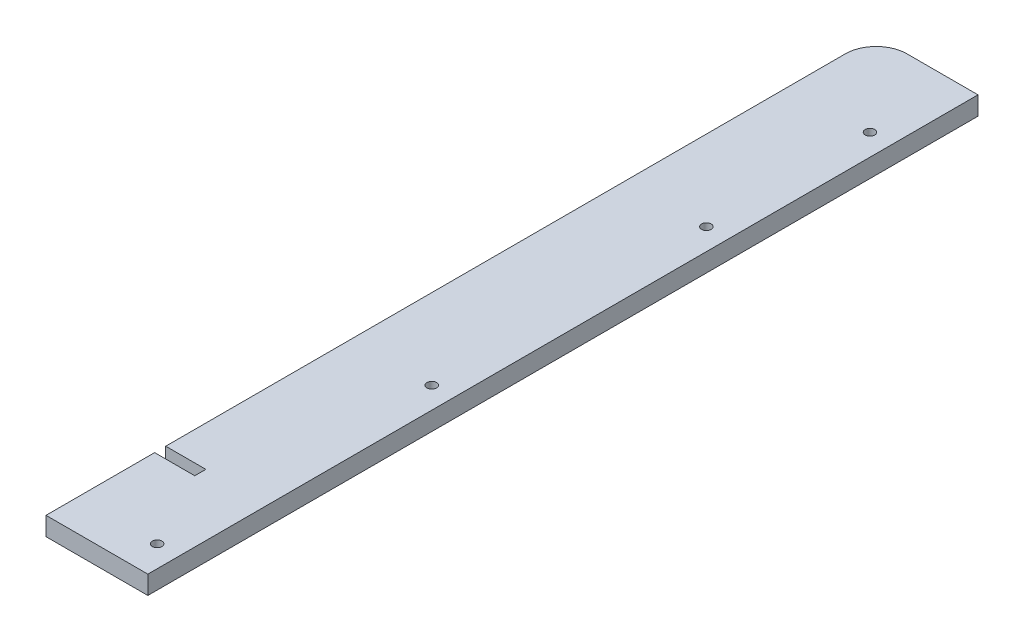
SolidWorks part; units mm, degrees
ref_plane "Płaszczyzna przednia" through (0, 0, 0) normal (0, 0, 1) x (1, 0, 0)
ref_plane "Płaszczyzna górna" through (0, 0, 0) normal (0, 1, 0) x (1, 0, 0)
ref_plane "Płaszczyzna prawa" through (0, 0, 0) normal (1, 0, 0) x (0, 0, -1)
sketch "Szkic2" plane through (0, 1505.9474, 0) normal (0, 1, 0) x (0, 0, 1)
  line L0 (-183.9552, 693.685) -> (-183.9552, -158.315)
  line L1 (-183.9552, 693.685) -> (103.0448, 693.685)
  line L2 (-183.9552, -158.315) -> (103.0448, -158.315)
  line L3 (103.0448, 693.685) -> (103.0448, -158.315)
  dimension "D1" = 852
  dimension "D2" = 287
extrude "Dodanie-wyciągnięcie1" add sketch "Szkic2" along normal blind 6
sketch "Szkic3" plane through (0, 1511.9474, 0) normal (0, 1, 0) x (1, 0, 0)
  line L14 (673.685, -83.0448) -> (673.685, 163.9552)
  line L15 (-138.315, -83.0448) -> (673.685, -83.0448)
  line L16 (673.685, 163.9552) -> (-138.315, 163.9552)
  line L17 (-138.315, 163.9552) -> (-138.315, -83.0448)
  line L18 (673.685, -73.0448) -> (673.685, 153.9552)
  line L19 (-128.315, -83.0448) -> (663.685, -83.0448)
  line L20 (663.685, 163.9552) -> (-128.315, 163.9552)
  line L21 (-138.315, 153.9552) -> (-138.315, -73.0448)
  arc A0 (673.685, 153.9552) -> (663.685, 163.9552) centre (663.685, 153.9552) ccw
  arc A1 (673.685, -73.0448) -> (663.685, -83.0448) centre (663.685, -73.0448) cw
  arc A2 (-128.315, -83.0448) -> (-138.315, -73.0448) centre (-128.315, -73.0448) cw
  arc A3 (-128.315, 163.9552) -> (-138.315, 153.9552) centre (-128.315, 153.9552) ccw
  dimension "D2" = 10
  dimension "D1" = 20
extrude "Wytnij-wyciągnięcie1" cut sketch "Szkic3" against normal blind 10
sketch "Szkic5" plane through (0, 1511.9474, 0) normal (0, 1, 0) x (1, 0, 0)
  line L0 (-158.315, -103.0448) -> (693.685, -103.0448) construction
  line L1 (-158.315, 183.9552) -> (-138.315, 183.9552)
  line L2 (-158.315, 183.9552) -> (-158.315, -103.0448)
  line L3 (-158.315, -103.0448) -> (-138.315, -103.0448)
  line L4 (-138.315, 183.9552) -> (-138.315, -103.0448)
  line L5 (-138.315, 153.9552) -> (-138.315, -73.0448) construction
  line L6 (693.685, 183.9552) -> (-158.315, 183.9552) construction
  dimension "D1" = 0
extrude "Wytnij-wyciągnięcie3" cut sketch "Szkic5" against normal through all flip side to cut
other "Przenieś ścianę1" face at (-158.315, 1508.9474, -40.4552) parameters "D1"=13
sketch "Szkic6" plane through (0, 1511.9474, 0) normal (0, 1, 0) x (1, 0, 0)
  line L0 (-138.315, 183.9552) -> (-138.315, -103.0448) construction
  line L1 (-171.315, 183.9552) -> (-138.315, 183.9552)
  line L2 (-171.315, 183.9552) -> (-171.315, 165.9552)
  line L3 (-171.315, 165.9552) -> (-138.315, 165.9552)
  line L4 (-138.315, 183.9552) -> (-138.315, 165.9552)
  dimension "D1" = 18
extrude "Wytnij-wyciągnięcie4" cut sketch "Szkic6" against normal blind 10
sketch "Szkic8" plane through (0, 1505.9474, 0) normal (0, -1, 0) x (1, 0, 0)
  line L0 (-161.315, -165.9552) -> (-171.315, -165.9552)
  line L2 (-171.315, -165.9552) -> (-171.315, -155.9552)
  arc A0 (-161.315, -165.9552) -> (-171.315, -155.9552) centre (-161.315, -155.9552) cw
  point P10 (-171.315, -165.9552)
  dimension "D1" = 10
extrude "Wytnij-wyciągnięcie6" cut sketch "Szkic8" against normal through all
sketch "Szkic9" plane through (0, 1511.9474, 0) normal (0, 1, 0) x (1, 0, 0)
  circle A0 centre (-145.315, -93.0448) radius 1.55 construction
  circle A1 centre (-145.315, -4.0448) radius 1.55 construction
  circle A2 centre (-145.315, 84.9552) radius 1.55 construction
  circle A3 centre (-145.315, 137.9552) radius 1.55 construction
  circle A4 centre (-145.315, 173.9552) radius 1.55 construction
  circle A5 centre (-145.315, -93.0448) radius 1.55
  circle A6 centre (-145.315, -4.0448) radius 1.55
  circle A7 centre (-145.315, 84.9552) radius 1.55
  circle A8 centre (-145.315, 137.9552) radius 1.55
  circle A9 centre (-145.315, 173.9552) radius 1.55
extrude "Wytnij-wyciągnięcie7" cut sketch "Szkic9" against normal blind 10
sketch "Szkic11" plane through (0, 1511.9474, 0) normal (0, 1, 0) x (1, 0, 0)
  line L0 (-171.315, -64.2448) -> (-158.315, -64.2448)
  line L1 (-171.315, -64.2448) -> (-171.315, -67.8448)
  line L2 (-158.315, -64.2448) -> (-158.315, -67.8448)
  line L3 (-171.315, -67.8448) -> (-158.315, -67.8448)
  line L4 (-171.315, 155.9552) -> (-171.315, -103.0448) construction
  line L5 (-171.315, -103.0448) -> (-138.315, -103.0448) construction
  dimension "D1" = 13
  dimension "D2" = 3.6
  dimension "D3" = 35.2
extrude "Wytnij-wyciągnięcie8" cut sketch "Szkic11" against normal blind 10
